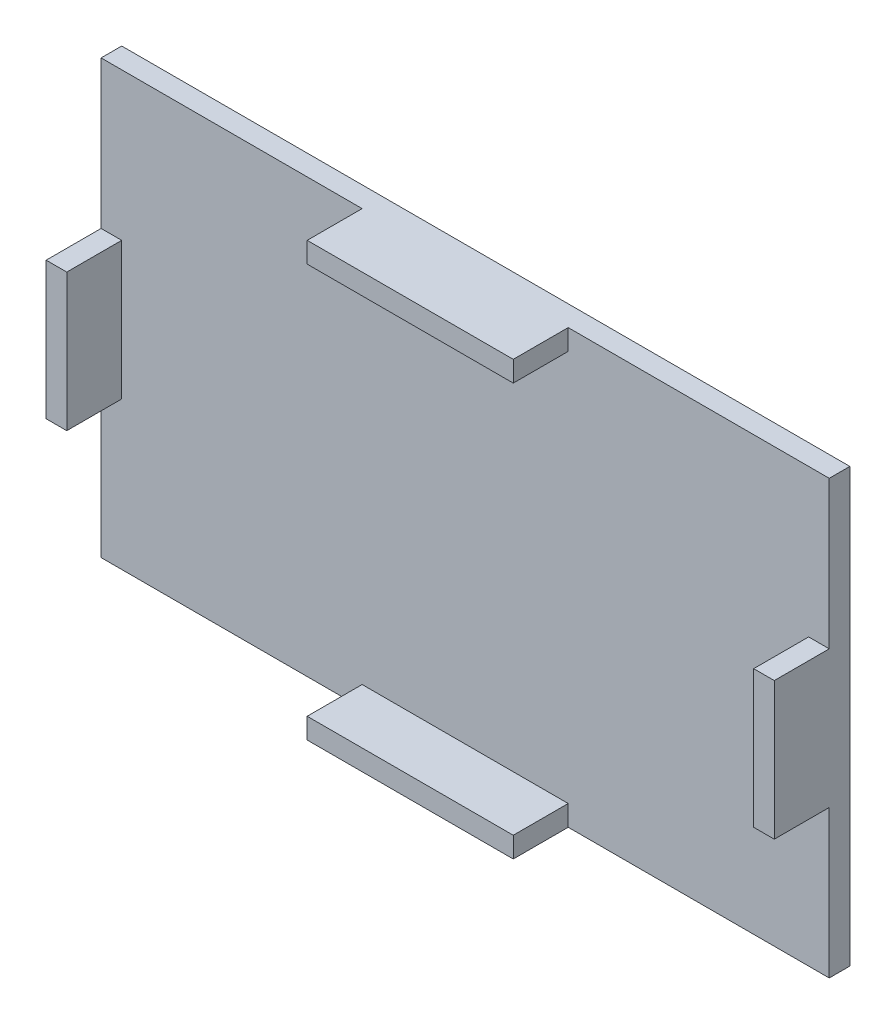
SolidWorks part; units mm, degrees
ref_plane "Front Plane" through (0, 0, 0) normal (0, 0, 1) x (1, 0, 0)
ref_plane "Top Plane" through (0, 0, 0) normal (0, 1, 0) x (1, 0, 0)
ref_plane "Right Plane" through (0, 0, 0) normal (1, 0, 0) x (0, 0, -1)
sketch "Sketch1" plane through (0, 0, 0) normal (0, 0, 1) x (1, 0, 0)
  line L0 (0, 0) -> (0, 31.5)
  line L1 (0, 31.5) -> (53, 31.5)
  line L2 (53, 31.5) -> (53, 0)
  line L3 (53, 0) -> (0, 0)
  dimension "D1" = 31.5
  dimension "D2" = 53
extrude "Boss-Extrude1" add sketch "Sketch1" along normal blind 1.5
sketch "Sketch2" plane through (0, 0, 1.5) normal (0, 0, 1) x (1, 0, 0)
  line L0 (0, 20.75) -> (1.5, 20.75)
  line L1 (0, 31.5) -> (0, 0) construction
  line L2 (1.5, 20.75) -> (1.5, 10.75)
  line L3 (1.5, 10.75) -> (0, 10.75)
  line L4 (0, 10.75) -> (0, 20.75)
  line L5 (19, 31.5) -> (19, 30)
  line L6 (53, 31.5) -> (0, 31.5) construction
  line L7 (19, 30) -> (34, 30)
  line L8 (34, 30) -> (34, 31.5)
  line L9 (34, 31.5) -> (19, 31.5)
  line L10 (53, 20.75) -> (51.5, 20.75)
  line L11 (53, 0) -> (53, 31.5) construction
  line L12 (51.5, 20.75) -> (51.5, 10.75)
  line L13 (51.5, 10.75) -> (53, 10.75)
  line L14 (34, 0) -> (34, 1.5)
  line L15 (0, 0) -> (53, 0) construction
  line L16 (34, 1.5) -> (19, 1.5)
  line L17 (19, 1.5) -> (19, 0)
  line L18 (19, 0) -> (34, 0)
  line L19 (53, 20.75) -> (53, 10.75)
  dimension "D1" = 1.5
  dimension "D2" = 15
  dimension "D3" = 19
  dimension "D4" = 1.5
  dimension "D5" = 19
  dimension "D6" = 15
  dimension "D7" = 1.5
  dimension "D8" = 10
  dimension "D9" = 10.75
  dimension "D10" = 1.5
  dimension "D11" = 10
extrude "Boss-Extrude2" add sketch "Sketch2" along normal blind 4
